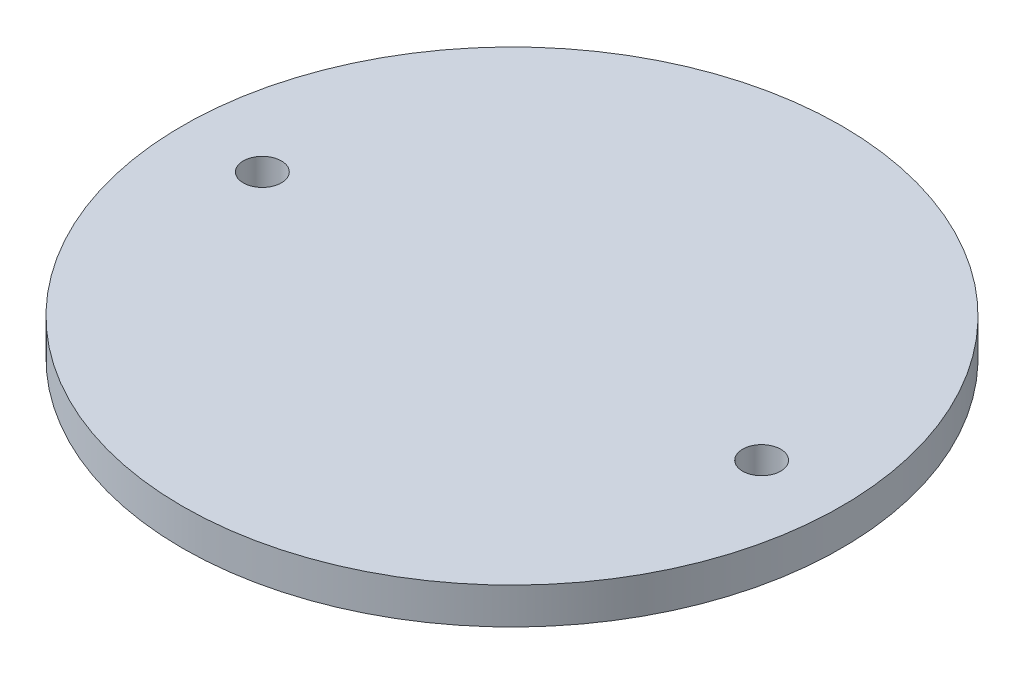
SolidWorks part; units mm, degrees
material "Balsa"
ref_plane "Front Plane" through (0, 0, 0) normal (0, 0, 1) x (1, 0, 0)
ref_plane "Top Plane" through (0, 0, 0) normal (0, 1, 0) x (1, 0, 0)
ref_plane "Right Plane" through (0, 0, 0) normal (1, 0, 0) x (0, 0, -1)
sketch "Sketch1" plane through (0, 0, 0) normal (0, 1, 0) x (1, 0, 0)
  line L0 (-36.3, 0) -> (36.3, 0) construction
  line L1 (0, 36.3) -> (0, -36.3) construction
  circle A0 centre (0, 0) radius 36.3
  circle A1 centre (-27.5, 0) radius 2.1
  circle A2 centre (27.5, 0) radius 2.1
  dimension "D1" = 55
  dimension "D2" = 72.6
  dimension "D3" = 4.2
extrude "Boss-Extrude1" add sketch "Sketch1" along normal blind 4
